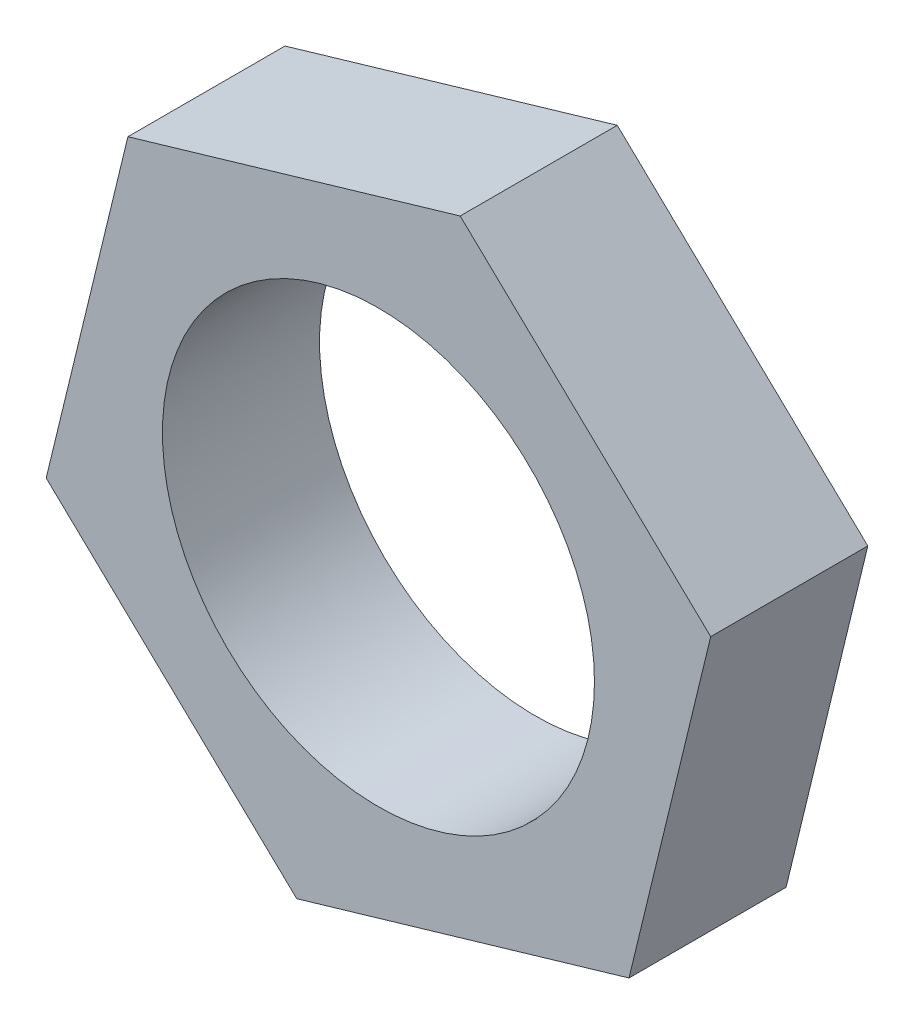
SolidWorks part; units mm, degrees
ref_plane "Alzado" through (0, 0, 0) normal (0, 0, 1) x (1, 0, 0)
ref_plane "Planta" through (0, 0, 0) normal (0, 1, 0) x (1, 0, 0)
ref_plane "Vista lateral" through (0, 0, 0) normal (1, 0, 0) x (0, 0, -1)
sketch "Croquis1" plane through (0, 0, 0) normal (0, 0, 1) x (1, 0, 0)
  line L0 (2.0808, 8.5677) -> (-6.3795, 6.0858)
  line L1 (-1.8082, -7.4456) -> (5.544, -5.2888) construction
  line L2 (5.544, -5.2888) -> (7.3522, 2.1568) construction
  line L3 (7.3522, 2.1568) -> (1.8082, 7.4456) construction
  line L4 (1.8082, 7.4456) -> (-5.544, 5.2888) construction
  line L5 (-5.544, 5.2888) -> (-7.3522, -2.1568) construction
  line L6 (-7.3522, -2.1568) -> (-1.8082, -7.4456) construction
  line L7 (-6.3795, 6.0858) -> (-8.4602, -2.4819)
  line L8 (-8.4602, -2.4819) -> (-2.0808, -8.5677)
  line L9 (-2.0808, -8.5677) -> (6.3795, -6.0858)
  line L10 (6.3795, -6.0858) -> (8.4602, 2.4819)
  line L11 (8.4602, 2.4819) -> (2.0808, 8.5677)
  circle A0 centre (0, 0) radius 5.5
  circle A1 centre (0, 0) radius 6.6355 construction
  dimension "D2" = 11
  dimension "D1" = 1
extrude "Saliente-Extruir1" add sketch "Croquis1" against normal blind 4
